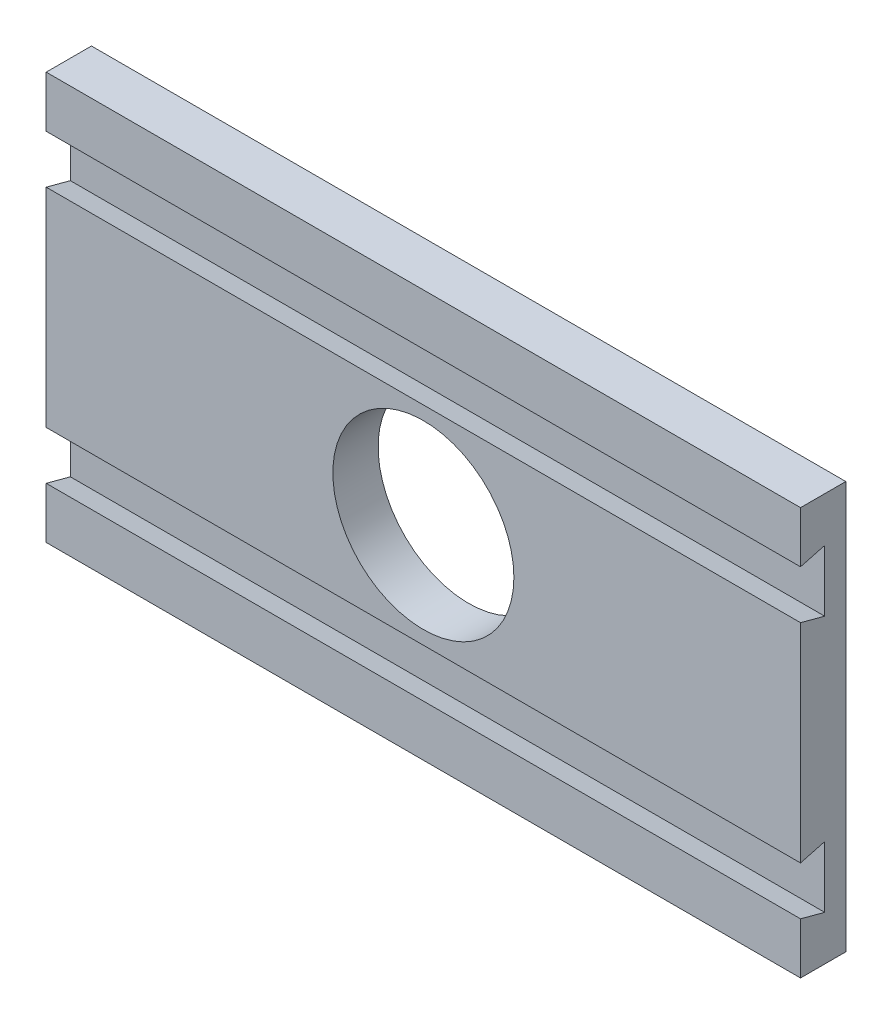
SolidWorks part; units mm, degrees
ref_plane "Front Plane" through (0, 0, 0) normal (0, 0, 1) x (1, 0, 0)
ref_plane "Top Plane" through (0, 0, 0) normal (0, 1, 0) x (1, 0, 0)
ref_plane "Right Plane" through (0, 0, 0) normal (1, 0, 0) x (0, 0, -1)
sketch "Plate profile" plane through (0, 0, 0) normal (0, 0, 1) x (1, 0, 0)
  line L0 (-50, -27) -> (50, -27)
  line L1 (50, -27) -> (50, 27)
  line L2 (50, 27) -> (-50, 27)
  line L3 (-50, 27) -> (-50, -27)
  circle A0 centre (0, 0) radius 12
extrude "Plate 6mm" add sketch "Plate profile" against normal blind 6 contours L2 L3 L0 L1
sketch "Groove profiles" plane through (0, 0, 0) normal (1, 0, 0) x (0, 0, -1)
  line L0 (-0.2, 13.8463) -> (3.2, 12.9397)
  line L1 (3.2, 12.9397) -> (3.2, 21.0603)
  line L2 (3.2, 21.0603) -> (-0.2, 20.1537)
  line L3 (-0.2, 20.1537) -> (-0.2, 13.8463)
  line L4 (-0.2, -13.8463) -> (3.2, -12.9397)
  line L5 (3.2, -12.9397) -> (3.2, -21.0603)
  line L6 (3.2, -21.0603) -> (-0.2, -20.1537)
  line L7 (-0.2, -20.1537) -> (-0.2, -13.8463)
extrude "Dovetail grooves" cut sketch "Groove profiles" against normal through all both and the other way through all
